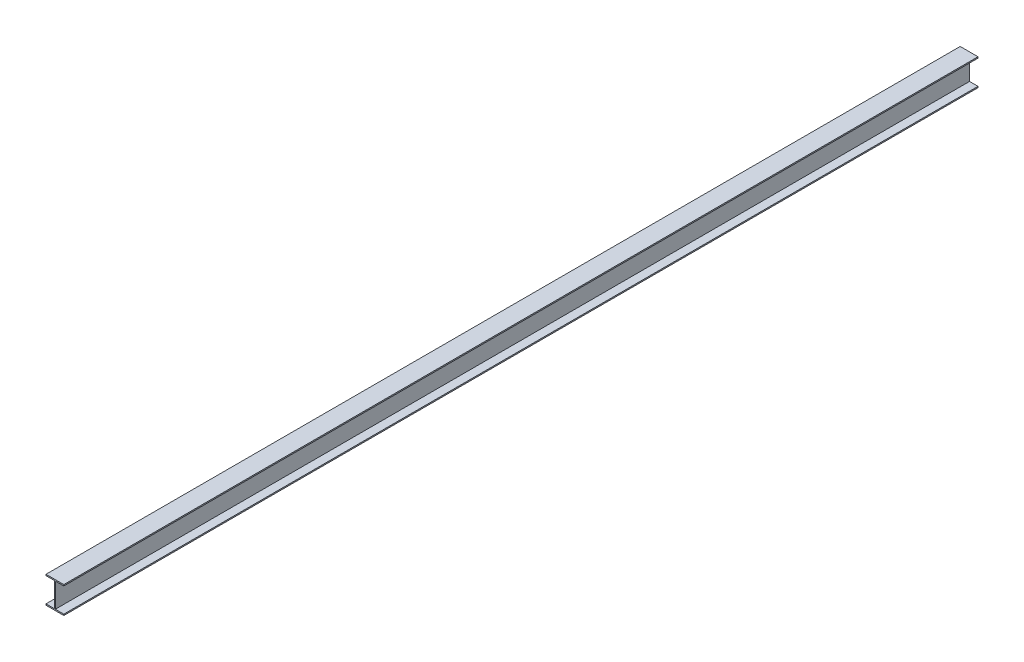
SolidWorks part; units mm, degrees
material "Alloy Steel"
ref_plane "Front" through (0, 0, 0) normal (0, 0, 1) x (1, 0, 0)
ref_plane "Top" through (0, 0, 0) normal (0, 1, 0) x (1, 0, 0)
ref_plane "Right" through (0, 0, 0) normal (1, 0, 0) x (0, 0, -1)
sketch "Sketch1" plane through (0, 0, 0) normal (0, 0, 1) x (1, 0, 0)
  line L0 (0, -0.0002) -> (101.6, -0.0002)
  line L1 (101.6, -0.0002) -> (101.6, -7.1122)
  line L2 (101.6, -7.1122) -> (53.408, -7.1122)
  line L3 (53.408, -7.1122) -> (53.408, -146.0502)
  line L4 (53.408, -146.0502) -> (101.6, -146.0502)
  line L5 (101.6, -146.0502) -> (101.6, -153.1622)
  line L6 (101.6, -153.1622) -> (0, -153.1622)
  line L7 (0, -153.1622) -> (0, -146.0502)
  line L8 (0, -146.0502) -> (47.566, -146.0502)
  line L9 (47.566, -146.0502) -> (47.566, -7.1122)
  line L10 (47.566, -7.1122) -> (0, -7.1122)
  line L11 (0, -7.1122) -> (0, -0.0002)
  line L12 (50.8, -0.0002) -> (50.8, -153.1622) construction
  dimension "D1" = 5.842
  dimension "D2" = 7.112
  dimension "D3" = 7.112
  dimension "D4" = 7.112
  dimension "D5" = 153.162
  dimension "D6" = 50.8
  dimension "D7" = 50.8
  dimension "D8" = 47.566
extrude "Boss-Extrude1" add sketch "Sketch1" along normal blind 5214.4
sketch "Sketch2" plane through (0, -153.1622, 0) normal (0, -1, 0) x (1, 0, 0)
  line L0 (0, 5214.4) -> (0, 0) construction
  line L1 (101.6, 5214.4) -> (101.6, 0) construction
  line L3 (101.6, 2607.2) -> (101.6, 2759.6)
  line L4 (101.6, 2759.6) -> (-279.5172, 2759.6)
  line L5 (-279.5172, 2607.2) -> (-279.5172, 2759.6)
  line L8 (101.6, 2607.2) -> (101.6, 2454.8)
  line L9 (101.6, 2454.8) -> (-279.5172, 2454.8)
  line L10 (-279.5172, 2607.2) -> (-279.5172, 2454.8)
  point P0 (0, 2607.2)
  dimension "D1" = 152.4
  dimension "D2" = 152.4
split line "Split Line1"
sketch "Sketch3" plane through (0, -153.1622, 0) normal (0, -1, 0) x (1, 0, 0)
  line L0 (0, 5214.4) -> (0, 2759.6) construction
  line L1 (1098.615, 304.8) -> (0, 304.8)
  line L2 (1098.615, 304.8) -> (1098.615, 0)
  line L3 (1098.615, 0) -> (0, 0)
  line L4 (0, 304.8) -> (0, 0)
  line L5 (1098.615, 5214.4) -> (0, 5214.4)
  line L6 (1098.615, 5214.4) -> (1098.615, 4909.6)
  line L7 (1098.615, 4909.6) -> (0, 4909.6)
  line L8 (0, 5214.4) -> (0, 4909.6)
split line "Split Line2"
